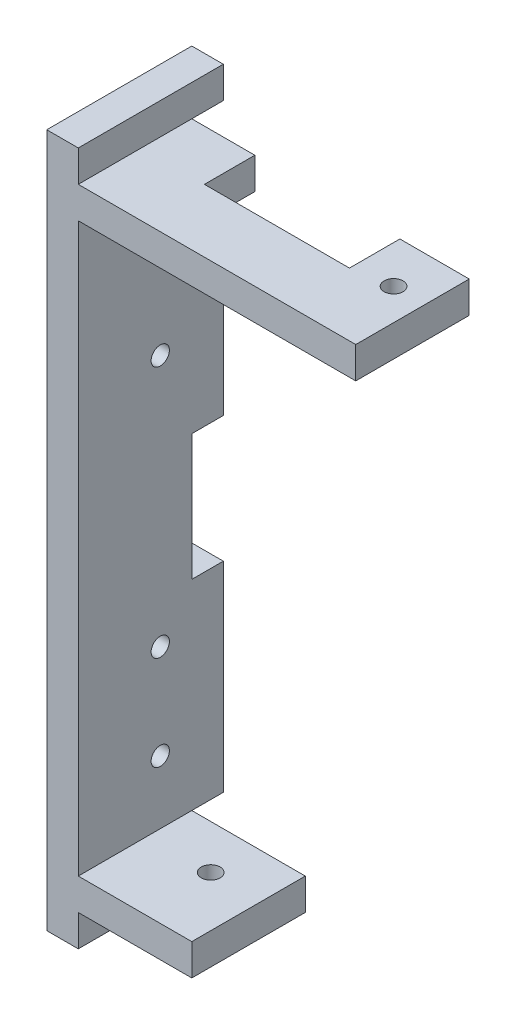
SolidWorks part; units mm, degrees
ref_plane "前基準面" through (0, 0, 0) normal (0, 0, 1) x (1, 0, 0)
ref_plane "上基準面" through (0, 0, 0) normal (0, 1, 0) x (1, 0, 0)
ref_plane "右基準面" through (0, 0, 0) normal (1, 0, 0) x (0, 0, -1)
sketch "草圖1" plane through (0, 0, 0) normal (0, 0, 1) x (1, 0, 0)
  line L0 (-17.4514, -4.6961) -> (-17.4514, -9.6961)
  line L1 (-22.4514, 100.3039) -> (-17.4514, 100.3039)
  line L2 (-22.4514, 100.3039) -> (-22.4514, -9.6961)
  line L3 (-22.4514, -9.6961) -> (-17.4514, -9.6961)
  line L4 (-17.4514, 100.3039) -> (-17.4514, 95.3039)
  line L5 (-17.4514, -4.6961) -> (0.5486, -4.6961)
  line L6 (-17.4514, 90.3039) -> (-17.4514, 0.3039)
  line L7 (-17.4514, 0.3039) -> (0.5486, 0.3039)
  line L8 (0.5486, -4.6961) -> (0.5486, 0.3039)
  line L9 (-17.4514, 95.3039) -> (26.5486, 95.3039)
  line L11 (-17.4514, 90.3039) -> (26.5486, 90.3039)
  line L12 (26.5486, 95.3039) -> (26.5486, 90.3039)
  dimension "D1" = 5
  dimension "D2" = 5
  dimension "D3" = 18
  dimension "D4" = 90
  dimension "D5" = 5
  dimension "D6" = 5
  dimension "D7" = 44
  dimension "D8" = 5
extrude "填料-伸長1" add sketch "草圖1" along normal blind 23
sketch "草圖2" plane through (0, 0, 0) normal (0, 0, -1) x (-1, 0, 0)
  line L0 (17.4514, 95.3039) -> (17.4514, 100.3039) construction
  line L1 (17.4514, 32.0539) -> (22.4514, 32.0539)
  line L2 (17.4514, 32.0539) -> (17.4514, 52.0539)
  line L3 (17.4514, 52.0539) -> (22.4514, 52.0539)
  line L4 (22.4514, 32.0539) -> (22.4514, 52.0539)
  line L5 (22.4514, 100.3039) -> (22.4514, -9.6961) construction
  line L6 (17.4514, 100.3039) -> (22.4514, 100.3039) construction
  dimension "D1" = 20
  dimension "D2" = 48.25
extrude "除料-伸長1" cut sketch "草圖2" against normal blind 5
sketch "草圖3" plane through (0, -4.6961, 0) normal (0, -1, 0) x (1, 0, 0)
  line L0 (-17.4514, 0) -> (0.5486, 0) construction
  line L2 (-17.4514, 23) -> (-17.4514, 0) construction
  circle A0 centre (-7.4514, 12) radius 1.5
  dimension "D1" = 3
  dimension "D2" = 12
  dimension "D3" = 10
sketch "草圖4" plane through (0, 95.3039, 0) normal (0, 1, 0) x (1, 0, 0)
  line L1 (-7.4514, 0) -> (15.5486, 0)
  line L2 (-7.4514, 0) -> (-7.4514, -13)
  line L3 (-7.4514, -13) -> (15.5486, -13)
  line L4 (15.5486, 0) -> (15.5486, -13)
  line L5 (-17.4514, -23) -> (-17.4514, 0) construction
  line L6 (26.5486, -23) -> (-17.4514, -23) construction
  line L8 (26.5486, 0) -> (-17.4514, 0) construction
  dimension "D1" = 10
  dimension "D2" = 10
  dimension "D3" = 23
extrude "除料-伸長2" cut sketch "草圖4" against normal up to next
extrude "除料-伸長3" cut sketch "草圖3" against normal up to next
sketch "草圖7" plane through (0, 95.3039, 0) normal (0, 1, 0) x (1, 0, 0)
  line L0 (26.5486, 0) -> (15.5486, 0) construction
  line L3 (15.5486, -13) -> (15.5486, 0) construction
  circle A0 centre (21.5486, -12) radius 1.5
  dimension "D1" = 3
  dimension "D2" = 12
  dimension "D3" = 6
extrude "除料-伸長4" cut sketch "草圖7" against normal through all
sketch "草圖8" plane through (0, 0, 0) normal (0, 0, -1) x (-1, 0, 0)
  line L1 (17.4514, 100.3039) -> (-58.6922, 100.3039)
  line L2 (17.4514, 100.3039) -> (17.4514, -13.3458)
  line L3 (17.4514, -13.3458) -> (-58.6922, -13.3458)
  line L4 (-58.6922, 100.3039) -> (-58.6922, -13.3458)
extrude "除料-伸長5" cut sketch "草圖8" against normal blind 5
sketch "草圖9" plane through (0, 0, 0) normal (0, 0, -1) x (-1, 0, 0)
  line L1 (17.4514, 95.3039) -> (45.4676, 95.3039)
  line L2 (17.4514, 95.3039) -> (17.4514, 90.3039)
  line L3 (17.4514, 90.3039) -> (45.4676, 90.3039)
  line L4 (45.4676, 95.3039) -> (45.4676, 90.3039)
  line L5 (17.4514, -4.6961) -> (57.6114, -4.6961)
  line L6 (17.4514, -4.6961) -> (17.4514, 0.3039)
  line L7 (17.4514, 0.3039) -> (57.6114, 0.3039)
  line L8 (57.6114, -4.6961) -> (57.6114, 0.3039)
  dimension "D1" = 5
  dimension "D2" = 5
extrude "除料-伸長6" cut sketch "草圖9" against normal blind 5
sketch "草圖10" plane through (-22.4514, 0, 0) normal (-1, 0, 0) x (0, 0, 1)
  line L0 (23, 100.3039) -> (0, 100.3039) construction
  line L1 (0, 90.3039) -> (0, 52.0539) construction
  line L2 (0, 32.0539) -> (0, 0.3039) construction
  line L3 (23, -9.6961) -> (0, -9.6961) construction
  circle A0 centre (10, 80.3039) radius 1.45
  circle A1 centre (10, 10.3039) radius 1.45
  circle A2 centre (10, 65.3039) radius 1.45
  circle A3 centre (10, 25.3039) radius 1.45
  point P18 (9.7262, 11.7278)
  dimension "D1" = 2.9
  dimension "D2" = 2.9
  dimension "D7" = 2.9
  dimension "D10" = 2.9
  dimension "D3" = 20
  dimension "D4" = 10
  dimension "D5" = 10
  dimension "D6" = 20
  dimension "D8" = 10
  dimension "D9" = 15
  dimension "D11" = 15
  dimension "D12" = 10
extrude "除料-伸長7" cut sketch "草圖10" against normal through all
